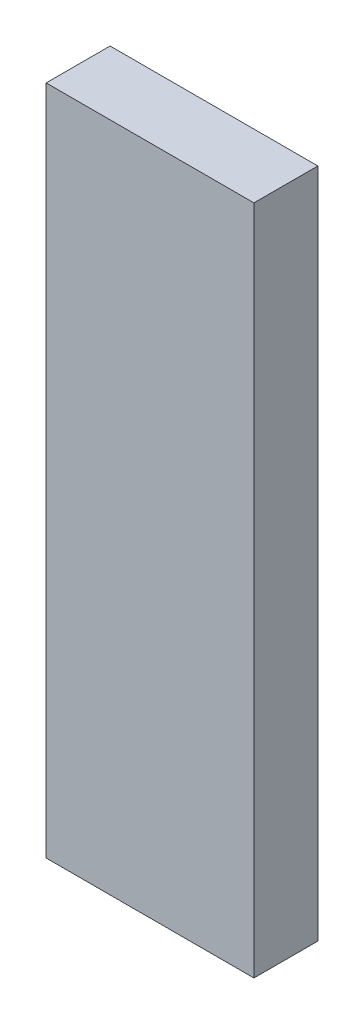
SolidWorks part; units mm, degrees
ref_plane "Front Plane" through (0, 0, 0) normal (0, 0, 1) x (1, 0, 0)
ref_plane "Top Plane" through (0, 0, 0) normal (0, 1, 0) x (1, 0, 0)
ref_plane "Right Plane" through (0, 0, 0) normal (1, 0, 0) x (0, 0, -1)
sketch "Sketch1" plane through (0, 0, 0) normal (0, 0, 1) x (1, 0, 0)
  line L1 (-32.5, -105) -> (32.5, -105)
  line L2 (-32.5, -105) -> (-32.5, 105)
  line L3 (-32.5, 105) -> (32.5, 105)
  line L4 (32.5, -105) -> (32.5, 105)
  line L5 (-32.5, -105) -> (32.5, 105) construction
  line L6 (-32.5, 105) -> (32.5, -105) construction
  point P0 (0, 0)
  dimension "D1" = 65
  dimension "D2" = 210
extrude "Boss-Extrude1" add sketch "Sketch1" along normal blind 20
